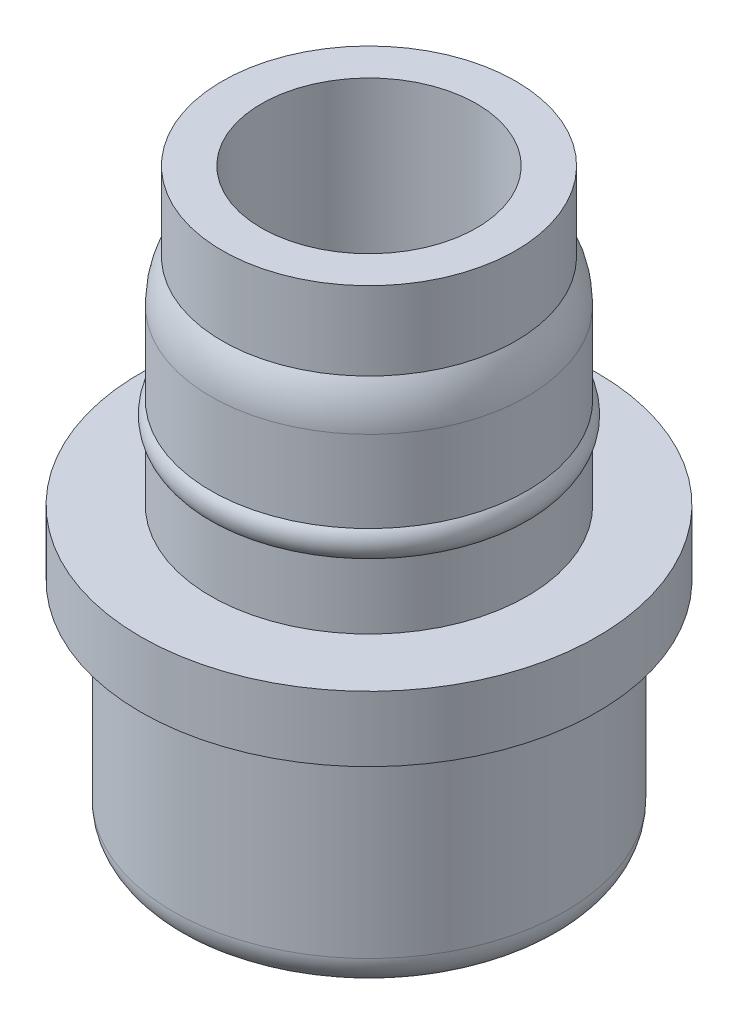
SolidWorks part; units mm, degrees
material "Nylon 6/10"
ref_plane "Front" through (0, 0, 0) normal (0, 0, 1) x (1, 0, 0)
ref_plane "Top" through (0, 0, 0) normal (0, 1, 0) x (1, 0, 0)
ref_plane "Right" through (0, 0, 0) normal (1, 0, 0) x (0, 0, -1)
sketch "Sketch1" plane through (0, 0, 0) normal (0, 0, 1) x (1, 0, 0)
  line L0 (0, 0) -> (0, 34.1936) construction
  line L1 (4.0792, -1.9) -> (5, -1.9)
  line L2 (6, -0.9) -> (6, 4.9)
  line L3 (6, 4.9) -> (7, 4.9)
  line L4 (7, 4.9) -> (7, 6.9)
  line L5 (7, 6.9) -> (4.85, 6.9)
  line L6 (4.85, 6.9) -> (4.85, 8.9)
  line L7 (4.85, 9.7) -> (4.85, 12.2)
  line L8 (4.5, 13.5) -> (4.5, 15.9)
  line L9 (4.5, 15.9) -> (3.3, 15.9)
  line L10 (3.3, 15.9) -> (3.3, 4.2)
  line L11 (0, 4.2) -> (0, 4.5)
  line L12 (1.6155, 4.2) -> (3.3, 4.2)
  line L13 (0, 4.2) -> (0, -4.5)
  arc A0 (0, -4.5) -> (4.0792, -1.9) centre (0, 0) ccw
  arc A1 (5, -1.9) -> (6, -0.9) centre (5, -0.9) ccw
  arc A2 (4.85, 8.9) -> (4.85, 9.7) centre (4.3917, 9.3) ccw
  arc A3 (4.85, 12.2) -> (4.5, 13.5) centre (2.2607, 12.2) ccw
  arc A4 (1.6155, 4.2) -> (0, 4.5) centre (0, 0) ccw
  dimension "D1" = 9
  dimension "D17" = 1
  dimension "D2" = 9
  dimension "D3" = 1.2
  dimension "D4" = 2.4
  dimension "D5" = 6.2
  dimension "D6" = 0.8
  dimension "D7" = 9
  dimension "D8" = 2
  dimension "D9" = 17.8
  dimension "D10" = 9.7
  dimension "D11" = 20.4
  dimension "D12" = 14
  dimension "D13" = 12
  dimension "D14" = 1.3
  dimension "D15" = 10
  dimension "D16" = 11.7
revolve "Revolve1" add sketch "Sketch1" angle 360 about L0
